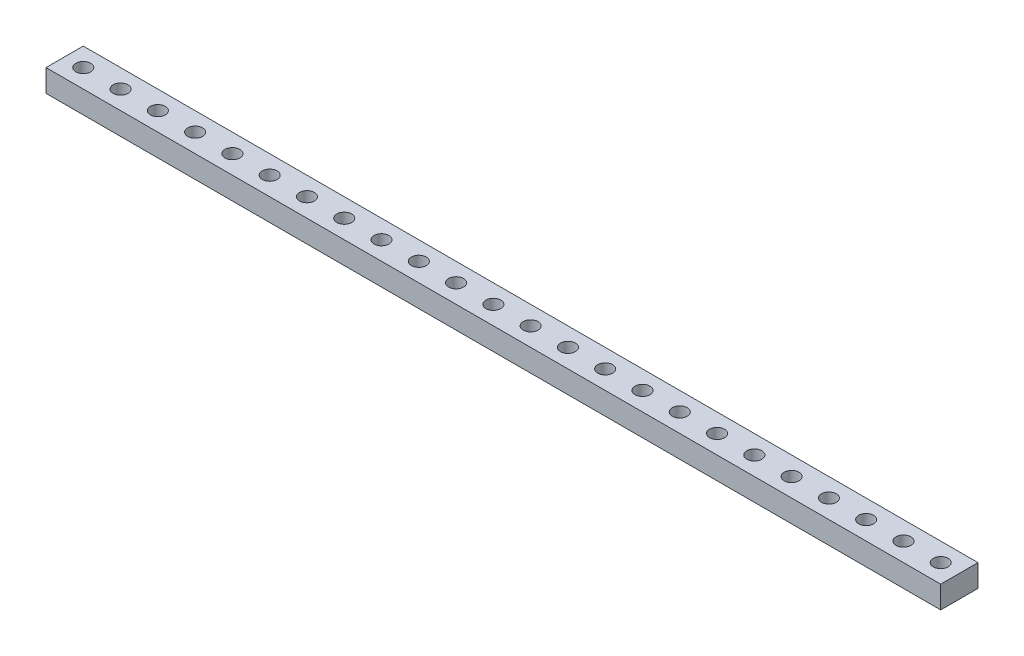
SolidWorks part; units mm, degrees
ref_plane "Plan de face" through (0, 0, 0) normal (0, 0, 1) x (1, 0, 0)
ref_plane "Plan de dessus" through (0, 0, 0) normal (0, 1, 0) x (1, 0, 0)
ref_plane "Plan de droite" through (0, 0, 0) normal (1, 0, 0) x (0, 0, -1)
sketch "Esquisse1" plane through (0, 0, 0) normal (0, 1, 0) x (1, 0, 0)
  line L0 (0, 0) -> (140, 0)
  line L1 (0, 0) -> (-140, 0)
  line L2 (-140, 0) -> (-140, 10)
  line L3 (-140, 10) -> (140, 10)
  line L4 (140, 10) -> (140, 0)
  line L5 (-140, 5) -> (-135, 5) construction
  circle A0 centre (-135, 5) radius 2
  circle A1 centre (-125, 5) radius 2
  circle A2 centre (-115, 5) radius 2
  circle A3 centre (-105, 5) radius 2
  circle A4 centre (-95, 5) radius 2
  circle A5 centre (-85, 5) radius 2
  circle A6 centre (-75, 5) radius 2
  circle A7 centre (-65, 5) radius 2
  circle A8 centre (-55, 5) radius 2
  circle A9 centre (-45, 5) radius 2
  circle A10 centre (-35, 5) radius 2
  circle A11 centre (-25, 5) radius 2
  circle A12 centre (-15, 5) radius 2
  circle A13 centre (-5, 5) radius 2
  circle A14 centre (5, 5) radius 2
  circle A15 centre (15, 5) radius 2
  circle A16 centre (25, 5) radius 2
  circle A17 centre (35, 5) radius 2
  circle A18 centre (45, 5) radius 2
  circle A19 centre (55, 5) radius 2
  circle A20 centre (65, 5) radius 2
  circle A21 centre (75, 5) radius 2
  circle A22 centre (85, 5) radius 2
  circle A23 centre (95, 5) radius 2
  circle A24 centre (105, 5) radius 2
  circle A25 centre (115, 5) radius 2
  circle A26 centre (125, 5) radius 2
  circle A27 centre (135, 5) radius 2
  dimension "D3" = 28
  dimension "D1" = 140
  dimension "D2" = 140
extrude "Boss.-Extru.1" add sketch "Esquisse1" along normal blind 6
sketch "Esquisse2" plane through (0, 6, 0) normal (0, 1, 0) x (1, 0, 0)
  line L0 (-140, 10) -> (100, 10) construction
  line L1 (140, 10) -> (-140, 10) construction
  line L2 (100, 10) -> (100, 0)
  line L3 (-140, 0) -> (140, 0) construction
  line L4 (100, 0) -> (140, 0)
  line L5 (140, 0) -> (140, 10)
  line L6 (140, 10) -> (100, 10)
extrude "Enlèv. mat.-Extru.1" cut sketch "Esquisse2" against normal up to next
